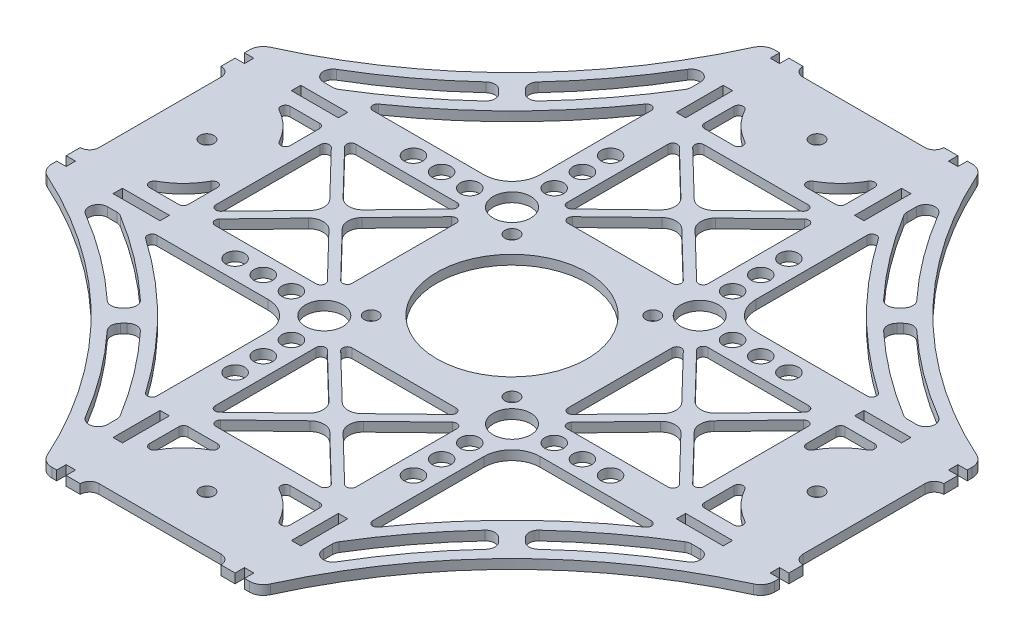
SolidWorks part; units mm, degrees
ref_plane "Front Plane" through (0, 0, 0) normal (0, 0, 1) x (1, 0, 0)
ref_plane "Top Plane" through (0, 0, 0) normal (0, 1, 0) x (1, 0, 0)
ref_plane "Right Plane" through (0, 0, 0) normal (1, 0, 0) x (0, 0, -1)
sketch "Sketch1" plane through (0, 0, 0) normal (0, 1, 0) x (1, 0, 0)
  line L0 (-21.0476, 77) -> (-20, 77)
  line L1 (0, 100.25) -> (0, 0) construction
  line L2 (0, 0) -> (109.75, 0) construction
  line L3 (0, 0) -> (220.1589, 220.1589) construction
  line L4 (77, 21.0476) -> (77, 20)
  line L5 (21.0476, -77) -> (20, -77)
  line L6 (-77, -21.0476) -> (-77, -20)
  line L7 (-20, 77) -> (-20, 75)
  line L8 (-20, 75) -> (-18, 75)
  line L9 (-18, 75) -> (-18, 77)
  line L10 (20, 77) -> (20, 75)
  line L11 (20, 75) -> (18, 75)
  line L12 (18, 75) -> (18, 77)
  line L13 (-13, 75) -> (13, 75)
  line L14 (23, 52.6783) -> (23, 29)
  line L15 (29, 23) -> (52.6783, 23)
  line L16 (77, 20) -> (75, 20)
  line L17 (75, 20) -> (75, 18)
  line L18 (75, 18) -> (77, 18)
  line L19 (52.6783, -23) -> (29, -23)
  line L20 (75, 13) -> (75, -13)
  line L21 (23, -29) -> (23, -52.6783)
  line L22 (75, -18) -> (77, -18)
  line L23 (75, -20) -> (75, -18)
  line L24 (77, -20) -> (75, -20)
  line L25 (20, -77) -> (20, -75)
  line L26 (20, -75) -> (18, -75)
  line L27 (18, -75) -> (18, -77)
  line L28 (-23, -52.6783) -> (-23, -29)
  line L29 (13, -75) -> (-13, -75)
  line L30 (-29, -23) -> (-52.6783, -23)
  line L31 (-18, -75) -> (-18, -77)
  line L32 (-20, -75) -> (-18, -75)
  line L33 (-20, -77) -> (-20, -75)
  line L34 (-77, -20) -> (-75, -20)
  line L35 (-75, -20) -> (-75, -18)
  line L36 (-75, -18) -> (-77, -18)
  line L37 (-52.6783, 23) -> (-29, 23)
  line L38 (-75, -13) -> (-75, 13)
  line L39 (-23, 29) -> (-23, 52.6783)
  line L40 (-75, 18) -> (-77, 18)
  line L41 (-75, 20) -> (-75, 18)
  line L42 (-77, 20) -> (-75, 20)
  line L43 (-18, 77) -> (-15, 77)
  line L44 (15, 77) -> (18, 77)
  line L45 (20, 77) -> (21.0476, 77)
  line L46 (77, 18) -> (77, 15)
  line L47 (77, -15) -> (77, -18)
  line L48 (77, -20) -> (77, -21.0476)
  line L49 (-20, -77) -> (-21.0476, -77)
  line L50 (-15, -77) -> (-18, -77)
  line L51 (18, -77) -> (15, -77)
  line L52 (-77, 20) -> (-77, 21.0476)
  line L53 (-77, 15) -> (-77, 18)
  line L54 (-77, -18) -> (-77, -15)
  line L55 (-15, 62.254) -> (-15, 56)
  line L56 (15, 62.254) -> (15, 56)
  line L57 (-14, 55) -> (-7.746, 55)
  line L58 (-11.0879, 52) -> (11.0879, 52)
  line L59 (-11.0879, 23) -> (11.0879, 23)
  line L60 (-15, 48.2516) -> (-15, 26.7484)
  line L61 (15, 48.2516) -> (15, 26.7484)
  line L62 (7.746, 55) -> (14, 55)
  line L63 (55, 14) -> (55, 7.746)
  line L64 (62.254, 15) -> (56, 15)
  line L65 (62.254, -15) -> (56, -15)
  line L66 (39.586, 42.4145) -> (40.2936, 43.1221)
  line L67 (23, 61.2099) -> (23, 63.1529)
  line L68 (61.2099, 23) -> (63.1529, 23)
  line L69 (42.4145, 39.586) -> (43.1221, 40.2936)
  line L70 (61.2099, -23) -> (63.1529, -23)
  line L71 (42.4145, -39.586) -> (43.1221, -40.2936)
  line L72 (39.586, -42.4145) -> (40.2936, -43.1221)
  line L73 (-62.254, 15) -> (-56, 15)
  line L74 (23, -61.2099) -> (23, -63.1529)
  line L75 (-23, -61.2099) -> (-23, -63.1529)
  line L76 (-39.586, -42.4145) -> (-40.2936, -43.1221)
  line L77 (-42.4145, -39.586) -> (-43.1221, -40.2936)
  line L78 (55, -7.746) -> (55, -14)
  line L79 (14, -55) -> (7.746, -55)
  line L80 (15, -62.254) -> (15, -56)
  line L81 (-15, -62.254) -> (-15, -56)
  line L82 (-7.746, -55) -> (-14, -55)
  line L83 (-55, -14) -> (-55, -7.746)
  line L84 (-62.254, -15) -> (-56, -15)
  line L85 (-61.2099, -23) -> (-63.1529, -23)
  line L86 (-55, 7.746) -> (-55, 14)
  line L87 (48.2516, 15) -> (26.7484, 15)
  line L88 (48.9706, 13.305) -> (39.657, 3.6701)
  line L89 (-13.305, 48.9706) -> (-3.6701, 39.657)
  line L90 (-11.7829, 24.719) -> (-2.0851, 34.0936)
  line L91 (-11.7829, 50.281) -> (-2.0851, 40.9064)
  line L92 (-13.305, 26.0294) -> (-3.6701, 35.343)
  line L93 (2.0851, 40.9064) -> (11.7829, 50.281)
  line L94 (26.0294, 13.305) -> (35.343, 3.6701)
  line L95 (24.719, 11.7829) -> (34.0936, 2.0851)
  line L96 (34.0936, -2.0851) -> (24.719, -11.7829)
  line L97 (23, 11.0879) -> (23, -11.0879)
  line L98 (48.2516, -15) -> (26.7484, -15)
  line L99 (35.343, -3.6701) -> (26.0294, -13.305)
  line L100 (3.6701, 35.343) -> (13.305, 26.0294)
  line L101 (3.6701, 39.657) -> (13.305, 48.9706)
  line L102 (2.0851, 34.0936) -> (11.7829, 24.719)
  line L103 (39.657, -3.6701) -> (48.9706, -13.305)
  line L104 (40.9064, -2.0851) -> (50.281, -11.7829)
  line L105 (50.281, 11.7829) -> (40.9064, 2.0851)
  line L106 (52, 11.0879) -> (52, -11.0879)
  line L107 (15, -48.2516) -> (15, -26.7484)
  line L108 (13.305, -48.9706) -> (3.6701, -39.657)
  line L109 (13.305, -26.0294) -> (3.6701, -35.343)
  line L110 (11.7829, -24.719) -> (2.0851, -34.0936)
  line L111 (-2.0851, -34.0936) -> (-11.7829, -24.719)
  line L112 (11.0879, -23) -> (-11.0879, -23)
  line L113 (-15, -48.2516) -> (-15, -26.7484)
  line L114 (-3.6701, -35.343) -> (-13.305, -26.0294)
  line L115 (-3.6701, -39.657) -> (-13.305, -48.9706)
  line L116 (-2.0851, -40.9064) -> (-11.7829, -50.281)
  line L117 (11.7829, -50.281) -> (2.0851, -40.9064)
  line L118 (11.0879, -52) -> (-11.0879, -52)
  line L119 (-48.2516, -15) -> (-26.7484, -15)
  line L120 (-48.9706, -13.305) -> (-39.657, -3.6701)
  line L121 (-26.0294, -13.305) -> (-35.343, -3.6701)
  line L122 (-24.719, -11.7829) -> (-34.0936, -2.0851)
  line L123 (-34.0936, 2.0851) -> (-24.719, 11.7829)
  line L124 (-23, -11.0879) -> (-23, 11.0879)
  line L125 (-48.2516, 15) -> (-26.7484, 15)
  line L126 (-35.343, 3.6701) -> (-26.0294, 13.305)
  line L127 (-39.657, 3.6701) -> (-48.9706, 13.305)
  line L128 (-40.9064, 2.0851) -> (-50.281, 11.7829)
  line L129 (-50.281, -11.7829) -> (-40.9064, -2.0851)
  line L130 (-52, -11.0879) -> (-52, 11.0879)
  line L131 (18, 55) -> (20, 55)
  line L132 (-18, 55) -> (-20, 55)
  line L133 (-18, 55) -> (-18, 65)
  line L134 (-18, 65) -> (-20, 65)
  line L135 (-20, 55) -> (-20, 65)
  line L136 (20, 55) -> (20, 65)
  line L137 (18, 65) -> (20, 65)
  line L138 (18, 55) -> (18, 65)
  line L139 (55, 20) -> (65, 20)
  line L140 (65, 18) -> (65, 20)
  line L141 (55, 18) -> (65, 18)
  line L142 (55, 18) -> (55, 20)
  line L143 (55, -18) -> (65, -18)
  line L144 (55, -18) -> (55, -20)
  line L145 (55, -20) -> (65, -20)
  line L146 (65, -18) -> (65, -20)
  line L147 (20, -55) -> (20, -65)
  line L148 (18, -65) -> (20, -65)
  line L149 (18, -55) -> (18, -65)
  line L150 (18, -55) -> (20, -55)
  line L151 (-18, -55) -> (-18, -65)
  line L152 (-18, -55) -> (-20, -55)
  line L153 (-20, -55) -> (-20, -65)
  line L154 (-18, -65) -> (-20, -65)
  line L155 (-55, -20) -> (-65, -20)
  line L156 (-65, -18) -> (-65, -20)
  line L157 (-55, -18) -> (-65, -18)
  line L158 (-55, -18) -> (-55, -20)
  line L159 (-55, 18) -> (-65, 18)
  line L160 (-55, 18) -> (-55, 20)
  line L161 (-55, 20) -> (-65, 20)
  line L162 (-65, 18) -> (-65, 20)
  line L163 (-61.2099, 23) -> (-63.1529, 23)
  line L164 (-42.4145, 39.586) -> (-43.1221, 40.2936)
  line L165 (-39.586, 42.4145) -> (-40.2936, 43.1221)
  line L166 (-23, 61.2099) -> (-23, 63.1529)
  circle A0 centre (0, 0) radius 16
  arc A1 (23.7793, 75.2401) -> (75.2401, 23.7793) centre (118.023, 118.023) ccw
  arc A2 (75.2401, -23.7793) -> (23.7793, -75.2401) centre (118.023, -118.023) ccw
  arc A3 (-23.7793, -75.2401) -> (-75.2401, -23.7793) centre (-118.023, -118.023) ccw
  arc A4 (-75.2401, 23.7793) -> (-23.7793, 75.2401) centre (-118.023, 118.023) ccw
  arc A5 (-13.125, 62.7382) -> (-7.2618, 56.875) centre (0, 70) ccw
  arc A6 (-15, 62.254) -> (-13.125, 62.7382) centre (-14, 62.254) cw
  arc A7 (15, 62.254) -> (13.125, 62.7382) centre (14, 62.254) ccw
  arc A8 (-14, 55) -> (-15, 56) centre (-14, 56) cw
  circle A9 centre (0, 65) radius 1.5
  arc A10 (14, 55) -> (15, 56) centre (14, 56) ccw
  arc A11 (-7.746, 55) -> (-7.2618, 56.875) centre (-7.746, 56) ccw
  arc A12 (7.746, 55) -> (7.2618, 56.875) centre (7.746, 56) cw
  arc A13 (7.2618, 56.875) -> (13.125, 62.7382) centre (0, 70) ccw
  arc A14 (62.254, 15) -> (62.7382, 13.125) centre (62.254, 14) cw
  arc A15 (62.7382, 13.125) -> (56.875, 7.2618) centre (70, 0) ccw
  arc A16 (55, 7.746) -> (56.875, 7.2618) centre (56, 7.746) ccw
  arc A17 (55, 14) -> (56, 15) centre (56, 14) cw
  arc A18 (55, -7.746) -> (56.875, -7.2618) centre (56, -7.746) cw
  arc A19 (56.875, -7.2618) -> (62.7382, -13.125) centre (70, 0) ccw
  arc A20 (62.254, -15) -> (62.7382, -13.125) centre (62.254, -14) ccw
  arc A21 (55, -14) -> (56, -15) centre (56, -14) ccw
  arc A22 (15, -62.254) -> (13.125, -62.7382) centre (14, -62.254) cw
  arc A23 (13.125, -62.7382) -> (7.2618, -56.875) centre (0, -70) ccw
  arc A24 (7.746, -55) -> (7.2618, -56.875) centre (7.746, -56) ccw
  arc A25 (14, -55) -> (15, -56) centre (14, -56) cw
  arc A26 (-7.746, -55) -> (-7.2618, -56.875) centre (-7.746, -56) cw
  arc A27 (-7.2618, -56.875) -> (-13.125, -62.7382) centre (0, -70) ccw
  arc A28 (-15, -62.254) -> (-13.125, -62.7382) centre (-14, -62.254) ccw
  arc A29 (-14, -55) -> (-15, -56) centre (-14, -56) ccw
  arc A30 (-62.254, -15) -> (-62.7382, -13.125) centre (-62.254, -14) cw
  arc A31 (-62.7382, -13.125) -> (-56.875, -7.2618) centre (-70, 0) ccw
  arc A32 (-55, -7.746) -> (-56.875, -7.2618) centre (-56, -7.746) ccw
  arc A33 (-55, -14) -> (-56, -15) centre (-56, -14) cw
  arc A34 (-55, 7.746) -> (-56.875, 7.2618) centre (-56, 7.746) cw
  arc A35 (-56.875, 7.2618) -> (-62.7382, 13.125) centre (-70, 0) ccw
  arc A36 (-62.254, 15) -> (-62.7382, 13.125) centre (-62.254, 14) ccw
  arc A37 (-55, 14) -> (-56, 15) centre (-56, 14) ccw
  arc A38 (24.8212, 53.249) -> (53.249, 24.8212) centre (118.023, 118.023) ccw
  arc A39 (52.6783, 23) -> (53.249, 24.8212) centre (52.6783, 24) ccw
  arc A40 (14.6736, 71.1065) -> (71.1065, 14.6736) centre (118.023, 118.023) ccw construction
  arc A41 (24.8212, 53.249) -> (23, 52.6783) centre (24, 52.6783) ccw
  arc A42 (23, 29) -> (29, 23) centre (29, 29) ccw
  arc A43 (53.249, -24.8212) -> (52.6783, -23) centre (52.6783, -24) ccw
  arc A44 (53.249, -24.8212) -> (24.8212, -53.249) centre (118.023, -118.023) ccw
  arc A45 (23, -52.6783) -> (24.8212, -53.249) centre (24, -52.6783) ccw
  circle A46 centre (65, 0) radius 1.5
  arc A47 (29, -23) -> (23, -29) centre (29, -29) ccw
  arc A48 (-24.8212, -53.249) -> (-23, -52.6783) centre (-24, -52.6783) ccw
  arc A49 (-24.8212, -53.249) -> (-53.249, -24.8212) centre (-118.023, -118.023) ccw
  arc A50 (-52.6783, -23) -> (-53.249, -24.8212) centre (-52.6783, -24) ccw
  arc A51 (-23, -29) -> (-29, -23) centre (-29, -29) ccw
  arc A52 (-53.249, 24.8212) -> (-52.6783, 23) centre (-52.6783, 24) ccw
  arc A53 (-53.249, 24.8212) -> (-24.8212, 53.249) centre (-118.023, 118.023) ccw
  arc A54 (-23, 52.6783) -> (-24.8212, 53.249) centre (-24, 52.6783) ccw
  circle A55 centre (0, -65) radius 1.5
  arc A56 (-29, 23) -> (-23, 29) centre (-29, 29) ccw
  circle A57 centre (20, 20) radius 4
  circle A58 centre (15, 15) radius 1.5
  circle A59 centre (19, 28) radius 2
  circle A60 centre (19, 34) radius 2
  circle A61 centre (19, 40) radius 2
  circle A62 centre (28, 19) radius 2
  circle A63 centre (34, 19) radius 2
  circle A64 centre (-65, 0) radius 1.5
  arc A65 (15, -48.2516) -> (13.305, -48.9706) centre (14, -48.2516) cw
  arc A66 (11.7829, -50.281) -> (11.0879, -52) centre (11.0879, -51) cw
  arc A67 (-11.7829, -50.281) -> (-11.0879, -52) centre (-11.0879, -51) ccw
  arc A68 (-15, -48.2516) -> (-13.305, -48.9706) centre (-14, -48.2516) ccw
  arc A69 (-15, -26.7484) -> (-13.305, -26.0294) centre (-14, -26.7484) cw
  arc A70 (15, -26.7484) -> (13.305, -26.0294) centre (14, -26.7484) ccw
  arc A71 (-11.7829, -24.719) -> (-11.0879, -23) centre (-11.0879, -24) cw
  arc A72 (11.7829, -24.719) -> (11.0879, -23) centre (11.0879, -24) ccw
  arc A73 (26.7484, -15) -> (26.0294, -13.305) centre (26.7484, -14) cw
  arc A74 (24.719, -11.7829) -> (23, -11.0879) centre (24, -11.0879) cw
  arc A75 (24.719, 11.7829) -> (23, 11.0879) centre (24, 11.0879) ccw
  arc A76 (26.7484, 15) -> (26.0294, 13.305) centre (26.7484, 14) ccw
  arc A77 (48.2516, 15) -> (48.9706, 13.305) centre (48.2516, 14) cw
  arc A78 (50.281, 11.7829) -> (52, 11.0879) centre (51, 11.0879) cw
  arc A79 (50.281, -11.7829) -> (52, -11.0879) centre (51, -11.0879) ccw
  arc A80 (48.2516, -15) -> (48.9706, -13.305) centre (48.2516, -14) ccw
  arc A81 (-26.7484, -15) -> (-26.0294, -13.305) centre (-26.7484, -14) ccw
  arc A82 (-24.719, -11.7829) -> (-23, -11.0879) centre (-24, -11.0879) ccw
  arc A83 (-24.719, 11.7829) -> (-23, 11.0879) centre (-24, 11.0879) cw
  arc A84 (-26.7484, 15) -> (-26.0294, 13.305) centre (-26.7484, 14) cw
  arc A85 (-48.2516, 15) -> (-48.9706, 13.305) centre (-48.2516, 14) ccw
  arc A86 (-50.281, 11.7829) -> (-52, 11.0879) centre (-51, 11.0879) ccw
  arc A87 (-50.281, -11.7829) -> (-52, -11.0879) centre (-51, -11.0879) cw
  arc A88 (-48.2516, -15) -> (-48.9706, -13.305) centre (-48.2516, -14) cw
  arc A89 (-13.305, 26.0294) -> (-15, 26.7484) centre (-14, 26.7484) cw
  arc A90 (-11.0879, 23) -> (-11.7829, 24.719) centre (-11.0879, 24) cw
  arc A91 (11.7829, 24.719) -> (11.0879, 23) centre (11.0879, 24) cw
  arc A92 (15, 26.7484) -> (13.305, 26.0294) centre (14, 26.7484) cw
  arc A93 (15, 48.2516) -> (13.305, 48.9706) centre (14, 48.2516) ccw
  arc A94 (11.7829, 50.281) -> (11.0879, 52) centre (11.0879, 51) ccw
  arc A95 (-11.7829, 50.281) -> (-11.0879, 52) centre (-11.0879, 51) cw
  arc A96 (-13.305, 48.9706) -> (-15, 48.2516) centre (-14, 48.2516) ccw
  arc A97 (3.6701, -39.657) -> (3.6701, -35.343) centre (5.7552, -37.5) cw
  arc A98 (-2.0851, -40.9064) -> (2.0851, -40.9064) centre (0, -43.0634) cw
  arc A99 (-3.6701, -35.343) -> (-3.6701, -39.657) centre (-5.7552, -37.5) cw
  arc A100 (2.0851, -34.0936) -> (-2.0851, -34.0936) centre (0, -31.9366) cw
  arc A101 (40.9064, -2.0851) -> (40.9064, 2.0851) centre (43.0634, 0) cw
  arc A102 (39.657, 3.6701) -> (35.343, 3.6701) centre (37.5, 5.7552) cw
  arc A103 (34.0936, 2.0851) -> (34.0936, -2.0851) centre (31.9366, 0) cw
  arc A104 (35.343, -3.6701) -> (39.657, -3.6701) centre (37.5, -5.7552) cw
  arc A105 (-34.0936, -2.0851) -> (-34.0936, 2.0851) centre (-31.9366, 0) cw
  arc A106 (-35.343, 3.6701) -> (-39.657, 3.6701) centre (-37.5, 5.7552) cw
  arc A107 (-40.9064, 2.0851) -> (-40.9064, -2.0851) centre (-43.0634, 0) cw
  arc A108 (-39.657, -3.6701) -> (-35.343, -3.6701) centre (-37.5, -5.7552) cw
  arc A109 (3.6701, 35.343) -> (3.6701, 39.657) centre (5.7552, 37.5) cw
  arc A110 (-2.0851, 34.0936) -> (2.0851, 34.0936) centre (0, 31.9366) cw
  arc A111 (-3.6701, 39.657) -> (-3.6701, 35.343) centre (-5.7552, 37.5) cw
  arc A112 (2.0851, 40.9064) -> (-2.0851, 40.9064) centre (0, 43.0634) cw
  arc A113 (-77, 21.0476) -> (-75.2401, 23.7793) centre (-74, 21.0476) cw
  arc A114 (-77, -21.0476) -> (-75.2401, -23.7793) centre (-74, -21.0476) ccw
  arc A115 (-21.0476, -77) -> (-23.7793, -75.2401) centre (-21.0476, -74) cw
  arc A116 (21.0476, -77) -> (23.7793, -75.2401) centre (21.0476, -74) ccw
  arc A117 (77, -21.0476) -> (75.2401, -23.7793) centre (74, -21.0476) cw
  arc A118 (77, 21.0476) -> (75.2401, 23.7793) centre (74, 21.0476) ccw
  arc A119 (21.0476, 77) -> (23.7793, 75.2401) centre (21.0476, 74) cw
  arc A120 (-21.0476, 77) -> (-23.7793, 75.2401) centre (-21.0476, 74) ccw
  arc A121 (-15, 77) -> (-13, 75) centre (-13, 77) ccw
  arc A122 (15, 77) -> (13, 75) centre (13, 77) cw
  arc A123 (77, 15) -> (75, 13) centre (77, 13) ccw
  arc A124 (77, -15) -> (75, -13) centre (77, -13) cw
  arc A125 (15, -77) -> (13, -75) centre (13, -77) ccw
  arc A126 (-15, -77) -> (-13, -75) centre (-13, -77) cw
  arc A127 (-77, -15) -> (-75, -13) centre (-77, -13) ccw
  arc A128 (-77, 15) -> (-75, 13) centre (-77, 13) cw
  circle A129 centre (40, 19) radius 2
  circle A130 centre (19, -40) radius 2
  circle A131 centre (19, -34) radius 2
  circle A132 centre (19, -28) radius 2
  circle A133 centre (20, -20) radius 4
  circle A134 centre (28, -19) radius 2
  circle A135 centre (34, -19) radius 2
  circle A136 centre (40, -19) radius 2
  circle A137 centre (15, -15) radius 1.5
  circle A138 centre (-40, -19) radius 2
  circle A139 centre (-34, -19) radius 2
  circle A140 centre (-28, -19) radius 2
  circle A141 centre (-20, -20) radius 4
  circle A142 centre (-19, -28) radius 2
  circle A143 centre (-19, -34) radius 2
  circle A144 centre (-19, -40) radius 2
  circle A145 centre (-15, -15) radius 1.5
  circle A146 centre (-19, 40) radius 2
  circle A147 centre (-19, 34) radius 2
  circle A148 centre (-19, 28) radius 2
  circle A149 centre (-20, 20) radius 4
  circle A150 centre (-28, 19) radius 2
  circle A151 centre (-34, 19) radius 2
  circle A152 centre (-40, 19) radius 2
  circle A153 centre (-15, 15) radius 1.5
  arc A154 (26.7226, 64.169) -> (40.345, 45.8971) centre (118.023, 118.023) ccw
  arc A155 (23.2932, 60.1675) -> (36.7067, 42.4673) centre (118.023, 118.023) ccw
  arc A156 (45.8971, 40.345) -> (64.169, 26.7226) centre (118.023, 118.023) ccw
  arc A157 (16.95, 72.1399) -> (72.1399, 16.95) centre (118.023, 118.023) ccw construction
  arc A158 (21.5029, 74.2067) -> (74.2067, 21.5029) centre (118.023, 118.023) ccw construction
  arc A159 (42.4673, 36.7067) -> (60.1675, 23.2932) centre (118.023, 118.023) ccw
  arc A160 (42.4145, 39.586) -> (42.4673, 36.7067) centre (43.8287, 38.1718) ccw
  arc A161 (43.1221, 40.2936) -> (45.8971, 40.345) centre (44.5363, 38.8794) cw
  arc A162 (39.586, 42.4145) -> (36.7067, 42.4673) centre (38.1718, 43.8287) cw
  arc A163 (40.2936, 43.1221) -> (40.345, 45.8971) centre (38.8794, 44.5363) ccw
  arc A164 (23.2932, 60.1675) -> (23, 61.2099) centre (25, 61.2099) cw
  arc A165 (61.2099, 23) -> (60.1675, 23.2932) centre (61.2099, 25) cw
  arc A166 (64.169, 26.7226) -> (63.1529, 23) centre (63.1529, 25) cw
  arc A167 (26.7226, 64.169) -> (23, 63.1529) centre (25, 63.1529) ccw
  arc A168 (64.169, -26.7226) -> (63.1529, -23) centre (63.1529, -25) ccw
  arc A169 (64.169, -26.7226) -> (45.8971, -40.345) centre (118.023, -118.023) ccw
  arc A170 (60.1675, -23.2932) -> (42.4673, -36.7067) centre (118.023, -118.023) ccw
  arc A171 (60.1675, -23.2932) -> (61.2099, -23) centre (61.2099, -25) cw
  arc A172 (43.1221, -40.2936) -> (45.8971, -40.345) centre (44.5363, -38.8794) ccw
  arc A173 (42.4145, -39.586) -> (42.4673, -36.7067) centre (43.8287, -38.1718) cw
  arc A174 (40.2936, -43.1221) -> (40.345, -45.8971) centre (38.8794, -44.5363) cw
  arc A175 (39.586, -42.4145) -> (36.7067, -42.4673) centre (38.1718, -43.8287) ccw
  arc A176 (36.7067, -42.4673) -> (23.2932, -60.1675) centre (118.023, -118.023) ccw
  arc A177 (40.345, -45.8971) -> (26.7226, -64.169) centre (118.023, -118.023) ccw
  arc A178 (26.7226, -64.169) -> (23, -63.1529) centre (25, -63.1529) cw
  arc A179 (23, -61.2099) -> (23.2932, -60.1675) centre (25, -61.2099) cw
  arc A180 (-26.7226, -64.169) -> (-23, -63.1529) centre (-25, -63.1529) ccw
  arc A181 (-26.7226, -64.169) -> (-40.345, -45.8971) centre (-118.023, -118.023) ccw
  arc A182 (-23.2932, -60.1675) -> (-36.7067, -42.4673) centre (-118.023, -118.023) ccw
  arc A183 (-23.2932, -60.1675) -> (-23, -61.2099) centre (-25, -61.2099) cw
  arc A184 (-40.2936, -43.1221) -> (-40.345, -45.8971) centre (-38.8794, -44.5363) ccw
  arc A185 (-39.586, -42.4145) -> (-36.7067, -42.4673) centre (-38.1718, -43.8287) cw
  arc A186 (-43.1221, -40.2936) -> (-45.8971, -40.345) centre (-44.5363, -38.8794) cw
  arc A187 (-42.4145, -39.586) -> (-42.4673, -36.7067) centre (-43.8287, -38.1718) ccw
  arc A188 (-42.4673, -36.7067) -> (-60.1675, -23.2932) centre (-118.023, -118.023) ccw
  arc A189 (-45.8971, -40.345) -> (-64.169, -26.7226) centre (-118.023, -118.023) ccw
  arc A190 (-64.169, -26.7226) -> (-63.1529, -23) centre (-63.1529, -25) cw
  arc A191 (-61.2099, -23) -> (-60.1675, -23.2932) centre (-61.2099, -25) cw
  arc A192 (-64.169, 26.7226) -> (-63.1529, 23) centre (-63.1529, 25) ccw
  arc A193 (-64.169, 26.7226) -> (-45.8971, 40.345) centre (-118.023, 118.023) ccw
  arc A194 (-60.1675, 23.2932) -> (-42.4673, 36.7067) centre (-118.023, 118.023) ccw
  arc A195 (-60.1675, 23.2932) -> (-61.2099, 23) centre (-61.2099, 25) cw
  arc A196 (-43.1221, 40.2936) -> (-45.8971, 40.345) centre (-44.5363, 38.8794) ccw
  arc A197 (-42.4145, 39.586) -> (-42.4673, 36.7067) centre (-43.8287, 38.1718) cw
  arc A198 (-40.2936, 43.1221) -> (-40.345, 45.8971) centre (-38.8794, 44.5363) cw
  arc A199 (-39.586, 42.4145) -> (-36.7067, 42.4673) centre (-38.1718, 43.8287) ccw
  arc A200 (-36.7067, 42.4673) -> (-23.2932, 60.1675) centre (-118.023, 118.023) ccw
  arc A201 (-40.345, 45.8971) -> (-26.7226, 64.169) centre (-118.023, 118.023) ccw
  arc A202 (-26.7226, 64.169) -> (-23, 63.1529) centre (-25, 63.1529) cw
  arc A203 (-23, 61.2099) -> (-23.2932, 60.1675) centre (-25, 61.2099) cw
  point P17 (0, 0)
  point P28 (0, 0)
  point P33 (-15, 52)
  point P34 (15, 52)
  point P71 (0, 0)
  point P75 (-15, 23)
  point P76 (15, 23)
  point P77 (-15.695, 51.281)
  point P80 (-15, 70)
  point P83 (15, 70)
  point P84 (0, 0)
  point P94 (14.305, 22.281)
  point P95 (-14.305, 22.281)
  point P157 (0, 0)
  point P163 (23, 23)
  point P201 (0, 0)
  point P221 (0, 0)
  point P222 (15.695, 51.281)
  point P223 (-14.305, 52.719)
  point P224 (15.695, 23.719)
  point P225 (-15.695, 23.719)
  point P226 (14.305, 52.719)
  point P278 (0, 0)
  point P366 (1.4388, 37.5)
  point P369 (0, 36.1092)
  point P374 (0, 38.8908)
  point P410 (0, 0)
  point P420 (77, 23)
  point P423 (23, 77)
  point P449 (0, 0)
  point P489 (0, 0)
  point P503 (40.9611, 38.1326)
  point P506 (44.4972, 41.6688)
  point P600 (0, 0)
  point P601 (0, 0)
  dimension "D2" = 207
  dimension "D5" = 1
  dimension "D6" = 1
  dimension "D7" = 1
  dimension "D8" = 2
  dimension "D9" = 1
  dimension "D12" = 1
  dimension "D13" = 3
  dimension "D15" = 3
  dimension "D16" = 4
  dimension "D10" = 6
  dimension "D18" = 4
  dimension "D21" = 2
  dimension "D23" = 3
  dimension "D25" = 3
  dimension "D17" = 4
  dimension "D11" = 4
  dimension "D4" = 10
  dimension "D19" = 2.5
  dimension "D20" = 7.5
  dimension "D22" = 4
  dimension "D3" = 4
  dimension "D14" = 4
  dimension "D24" = 4
extrude "Boss-Extrude1" add sketch "Sketch1" along normal blind 2
